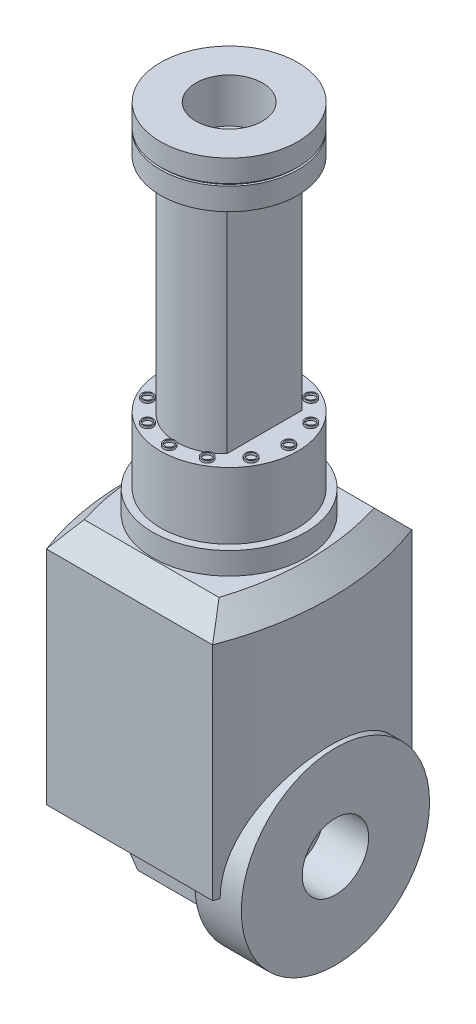
SolidWorks part; units mm, degrees
ref_plane "Front Plane" through (0, 0, 0) normal (0, 0, 1) x (1, 0, 0)
ref_plane "Top Plane" through (0, 0, 0) normal (0, 1, 0) x (1, 0, 0)
ref_plane "Right Plane" through (0, 0, 0) normal (1, 0, 0) x (0, 0, -1)
sketch "Sketch1" plane through (0, 0, 0) normal (0, 1, 0) x (1, 0, 0)
  line L0 (0, 97.4377) -> (0, -80.2709) construction
  line L1 (-78.5224, 0) -> (107.7696, 0) construction
  line L2 (-37.5, 45) -> (37.5, 45)
  line L3 (37.5, -45) -> (-37.5, -45)
  line L4 (78.5224, 0) -> (-107.7696, 0) construction
  arc A0 (37.5, 45) -> (37.5, -45) centre (-79.119, 0) cw
  arc A1 (-37.5, 45) -> (-37.5, -45) centre (79.119, 0) ccw
  point P11 (0, -45)
  point P12 (0, 45)
  dimension "D2" = 125
  dimension "D1" = 37.5
  dimension "D3" = 45
  dimension "D4" = 37.5
  dimension "D5" = 45
extrude "Boss-Extrude1" add sketch "Sketch1" along normal blind 100
sketch "Sketch2" plane through (0, 100, 0) normal (0, 1, 0) x (1, 0, 0)
  line L2 (37.5, 45) -> (-37.5, 45)
  line L3 (-37.5, -45) -> (37.5, -45)
  line L4 (37.5, 45) -> (-37.5, 45)
  line L5 (-37.5, -45) -> (37.5, -45)
  arc A2 (37.5, -45) -> (37.5, 45) centre (-79.119, 0) ccw
  arc A3 (-37.5, 45) -> (-37.5, -45) centre (79.119, 0) ccw
  arc A4 (37.5, -45) -> (37.5, 45) centre (-79.119, 0) ccw
  arc A5 (-37.5, 45) -> (-37.5, -45) centre (79.119, 0) ccw
  dimension "D1" = 0
extrude "Boss-Extrude2" add sketch "Sketch2" along normal blind 10 draft 45
sketch "Sketch3" plane through (0, 110, 0) normal (0, 1, 0) x (1, 0, 0)
  circle A0 centre (0, 0) radius 34.5
  dimension "D1" = 69
extrude "Boss-Extrude3" add sketch "Sketch3" along normal blind 10
sketch "Sketch4" plane through (0, 120, 0) normal (0, 1, 0) x (1, 0, 0)
  circle A0 centre (0, 0) radius 31
  dimension "D1" = 62
extrude "Boss-Extrude4" add sketch "Sketch4" along normal blind 30
sketch "Sketch5" plane through (0, 150, 0) normal (0, 1, 0) x (1, 0, 0)
  circle A0 centre (27, 0) radius 2.5
  circle A1 centre (27, 0) radius 2
  dimension "D2" = 5
  dimension "D3" = 4
  dimension "D1" = 27
extrude "Boss-Extrude5" add sketch "Sketch5" along normal blind 1
pattern_circular "CirPattern1" count 12 over 360 about axis through (0, 0, 0) along (0, 1, 0) of "Boss-Extrude5"
sketch "Sketch6" plane through (0, 150, 0) normal (0, 1, 0) x (1, 0, 0)
  line L0 (0, 15.3218) -> (0, -17.0587) construction
  line L1 (-20.5945, 0) -> (23.3239, 0) construction
  line L2 (16, 17) -> (16, -17)
  line L3 (-16, 17) -> (-16, -17)
  arc A0 (-16, 17) -> (16, 17) centre (0, 1.9003) cw
  arc A1 (-16, -17) -> (16, -17) centre (0, -1.9003) ccw
  dimension "D4" = 22
  dimension "D1" = 17
  dimension "D3" = 16
extrude "Boss-Extrude6" add sketch "Sketch6" along normal blind 100
sketch "Sketch7" plane through (0, 250, 0) normal (0, 1, 0) x (1, 0, 0)
  circle A0 centre (0, 0) radius 31
extrude "Boss-Extrude7" add sketch "Sketch7" along normal blind 10
sketch "Sketch8" plane through (0, 260, 0) normal (0, 1, 0) x (1, 0, 0)
  circle A0 centre (0, 0) radius 30
  circle A1 centre (0, 0) radius 31 construction
  dimension "D1" = 1
extrude "Boss-Extrude8" add sketch "Sketch8" along normal blind 1
sketch "Sketch9" plane through (0, 261, 0) normal (0, 1, 0) x (1, 0, 0)
  circle A0 centre (0, 0) radius 31
extrude "Boss-Extrude9" add sketch "Sketch9" along normal blind 10
ref_plane "Plane1" through (37.5, 0, 0) normal (-1, 0, 0) x (0, 0, 1)
sketch "Sketch11" plane through (37.5, 0, 0) normal (-1, 0, 0) x (0, 0, 1)
  circle A0 centre (0, 0) radius 42.5
  dimension "D1" = 85
extrude "Boss-Extrude10" add sketch "Sketch11" along normal mid plane 21
sketch "Sketch12" plane through (27, 0, 0) normal (-1, 0, 0) x (0, 0, 1)
  line L0 (-20, 0) -> (20, 0)
  line L1 (42.5, 0) -> (-42.5, 0) construction
  line L2 (-20, 0) -> (-20, -30)
  line L3 (20, 0) -> (20, -30)
  arc A0 (-20, -30) -> (20, -30) centre (0, -7.6393) ccw
  point P5 (0, 0)
  dimension "D4" = 30
  dimension "D1" = 40
  dimension "D2" = 30
  dimension "D3" = 30
extrude "Boss-Extrude11" add sketch "Sketch12" along normal blind 35
sketch "Sketch14" plane through (0, 0, -20) normal (0, 0, -1) x (-1, 0, 0)
  line L0 (8, 0) -> (8, -42)
  line L1 (8, 0) -> (33, 0)
  line L2 (-37.5, 0) -> (37.5, 0) construction
  arc A0 (33, 0) -> (8, -42) centre (-21.8393, 4.2019) cw
  dimension "D3" = 55
  dimension "D1" = 25
  dimension "D2" = 42
extrude "Boss-Extrude12" add sketch "Sketch14" against normal blind 40
sketch "Sketch15" plane through (-8, 0, 0) normal (1, 0, 0) x (0, 0, -1)
  line L3 (-20, -30) -> (-20, -42)
  line L4 (-20, -42) -> (20, -42)
  line L5 (20, -42) -> (20, -30)
  line L6 (-20, -30) -> (-20, -42)
  line L7 (-20, -42) -> (20, -42)
  line L8 (20, -42) -> (20, -30)
  arc A1 (-20, -30) -> (20, -30) centre (0, -7.6393) ccw
  arc A2 (-20, -30) -> (20, -30) centre (0, -7.6393) ccw
  dimension "D1" = 0
extrude "Cut-Extrude1" cut sketch "Sketch15" against normal blind 40
sketch "Sketch16" plane through (0, 271, 0) normal (0, 1, 0) x (1, 0, 0)
  circle A0 centre (0, 0) radius 15
  dimension "D1" = 30
extrude "Cut-Extrude2" cut sketch "Sketch16" against normal blind 20
sketch "Sketch17" plane through (48, 0, 0) normal (1, 0, 0) x (0, 0, -1)
  circle A0 centre (0, 0) radius 15
  dimension "D1" = 30
extrude "Cut-Extrude3" cut sketch "Sketch17" against normal blind 20
ref_plane "Plane2" through (37.5, 0, 0) normal (-1, 0, 0) x (0, 0, 1)
ref_point "Point1"
